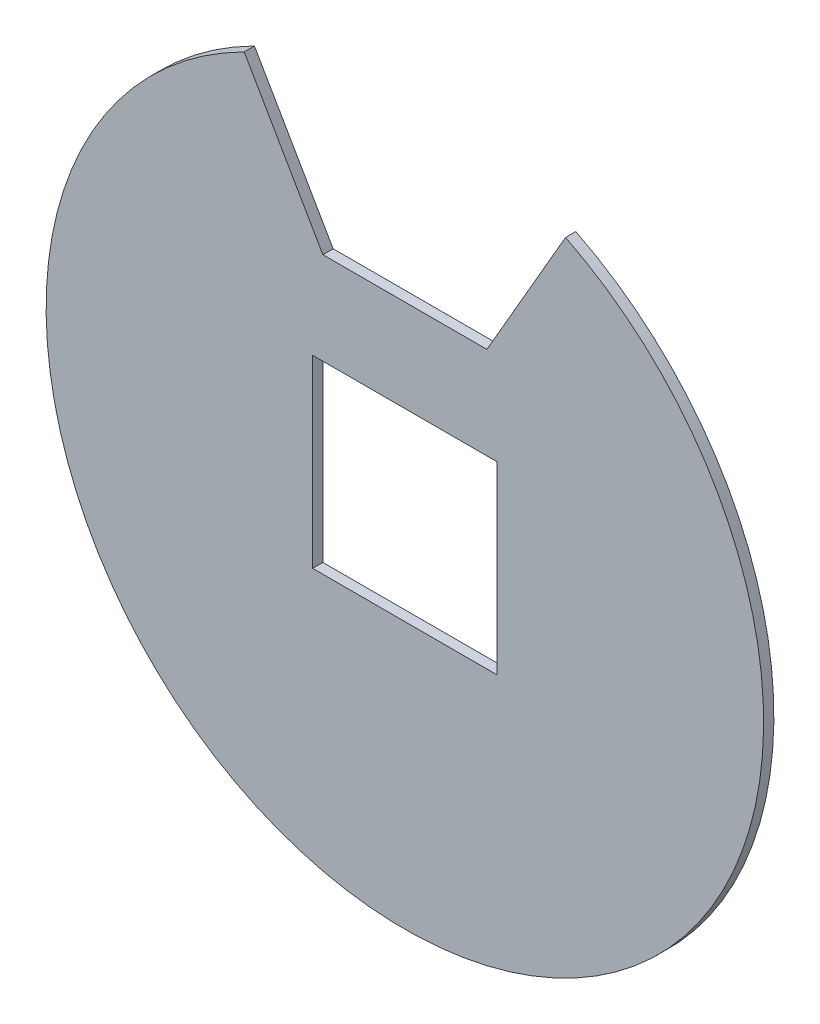
SolidWorks part; units mm, degrees
material "Balsa"
ref_plane "Plan de face" through (0, 0, 0) normal (0, 0, 1) x (1, 0, 0)
ref_plane "Plan de dessus" through (0, 0, 0) normal (0, 1, 0) x (1, 0, 0)
ref_plane "Plan de droite" through (0, 0, 0) normal (1, 0, 0) x (0, 0, -1)
sketch "Esquisse1" plane through (0, 0, 0) normal (0, 0, 1) x (1, 0, 0)
  line L0 (45, 45) -> (45, -45)
  line L1 (45, -45) -> (-45, -45)
  line L2 (-45, -45) -> (-45, 45)
  line L3 (-45, 45) -> (45, 45)
  line L8 (45, -45) -> (-45, 45) construction
  line L9 (-45, -45) -> (45, 45) construction
  circle A0 centre (0, 0) radius 175
  dimension "D2" = 350
  dimension "D3" = 90
  dimension "D1" = 90
extrude "Boss.-Extru.1" add sketch "Esquisse1" along normal blind 5
sketch "Esquisse2" plane through (0, 0, 5) normal (0, 0, 1) x (1, 0, 0)
  line L0 (0, 0) -> (0, 175) construction
  line L1 (78.3754, 156.4682) -> (40, 90)
  line L2 (0, -175) -> (0, 0) construction
  line L3 (40, 90) -> (-40, 90)
  line L4 (-40, 90) -> (-78.3754, 156.4682)
  circle A0 centre (0, 0) radius 175 construction
  arc A1 (78.3754, 156.4682) -> (-78.3754, 156.4682) centre (0, 20.718) ccw
  dimension "D2" = 80
  dimension "D1" = 0
  dimension "D3" = 90
  dimension "D4" = 120
extrude "Enlèv. mat.-Extru.1" cut sketch "Esquisse2" against normal blind 10
